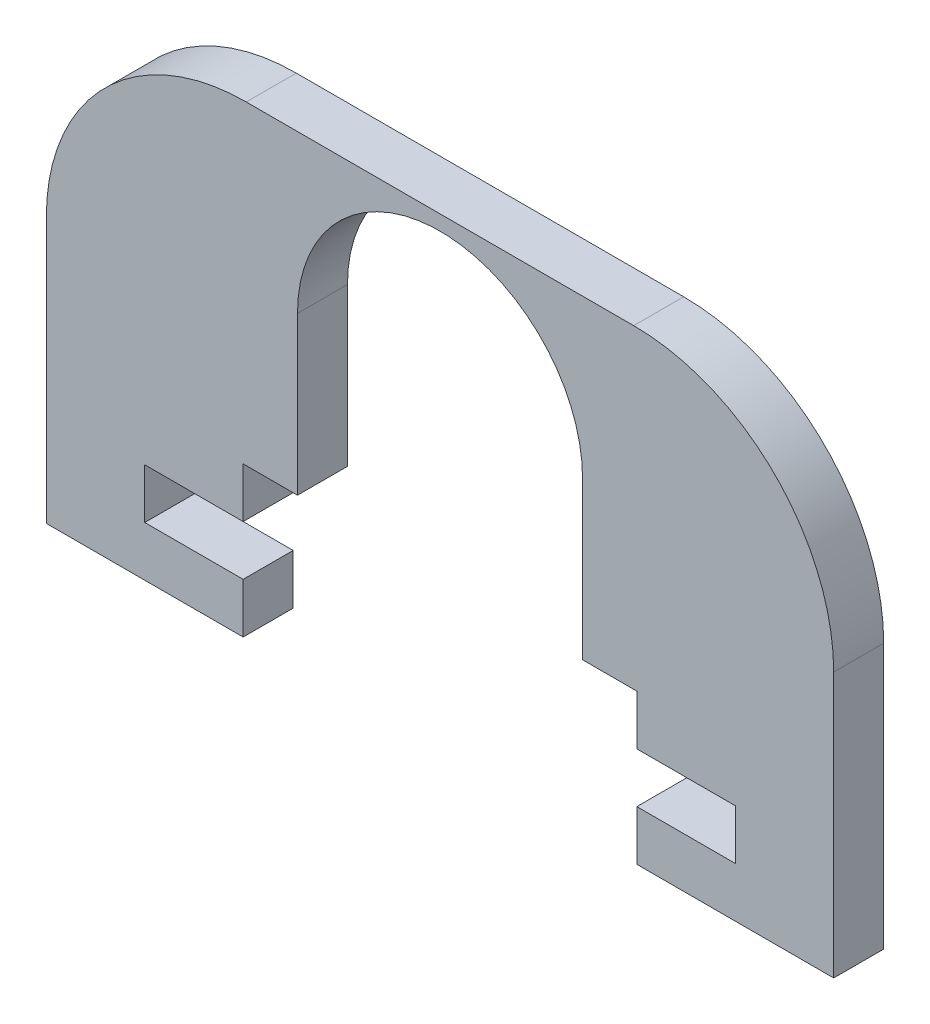
SolidWorks part; units mm, degrees
ref_plane "Front Plane" through (0, 0, 0) normal (0, 0, 1) x (1, 0, 0)
ref_plane "Top Plane" through (0, 0, 0) normal (0, 1, 0) x (1, 0, 0)
ref_plane "Right Plane" through (0, 0, 0) normal (1, 0, 0) x (0, 0, -1)
sketch "Sketch1" plane through (0, 0, 0) normal (0, 0, 1) x (1, 0, 0)
  line L0 (50, 40) -> (50, -12.5863) construction
  line L1 (25, 0) -> (75, 0)
  line L2 (0, 0) -> (0, 40)
  line L3 (0, 40) -> (100, 40)
  line L4 (100, 0) -> (100, 40)
  line L6 (0, 0) -> (0, -6.35)
  line L8 (25, 0) -> (25, -6.35)
  line L10 (75, 0) -> (75, -6.35)
  line L12 (100, 0) -> (100, -6.35)
  line L13 (0, -6.35) -> (0, -19.05)
  line L14 (0, -19.05) -> (25, -19.05)
  line L15 (25, -19.05) -> (25, -6.35)
  line L16 (100, -6.35) -> (100, -19.05)
  line L17 (75, -19.05) -> (75, -6.35)
  line L18 (100, -19.05) -> (75, -19.05)
  dimension "D1" = 100
  dimension "D2" = 40
  dimension "D3" = 6.35
  dimension "D4" = 6.35
  dimension "D5" = 25
  dimension "D6" = 12.7
extrude "Boss-Extrude1" add sketch "Sketch1" along normal blind 6.35
sketch "Sketch2" plane through (0, 0, 6.35) normal (0, 0, 1) x (1, 0, 0)
  line L0 (10, 57.1598) -> (10, -9.9345) construction
  line L1 (0, 40) -> (0, -19.05) construction
  line L2 (50, 0) -> (50, 61.0572) construction
  line L3 (25, 0) -> (75, 0) construction
  line L4 (90, 57.1598) -> (90, -9.9345) construction
  line L6 (100, 40) -> (0, 40) construction
  line L8 (31.921, 40) -> (67.8318, 40)
  line L9 (50, 38.1) -> (50, 6.0702) construction
  line L10 (31.9, 20) -> (68.1, 20) construction
  line L11 (31.9, 20) -> (31.9, 0)
  line L12 (68.1, 20) -> (68.1, 0)
  line L13 (31.9, 0) -> (68.1, 0)
  arc A1 (68.1, 20) -> (31.9, 20) centre (50, 20) ccw
  line M9 (25, 0) -> (75, 0)
  dimension "D2" = 36.2
  dimension "D1" = 10
  dimension "D3" = 20
extrude "Cut-Extrude1" cut sketch "Sketch2" against normal through all both and the other way through all contours L12 A1 L11 M9
fillet "Fillet1" radius 25.4 2 edges at (100, 40, 3.175) (0, 40, 3.175)
sketch "Sketch4" plane through (0, 0, 6.35) normal (0, 0, 1) x (1, 0, 0)
  line L0 (25, 0) -> (25, -6.35)
  line L1 (25, -19.05) -> (25, 0) construction
  line L2 (25, -6.35) -> (12.5, -6.35)
  line L3 (12.5, -6.35) -> (12.5, -12.7)
  line L4 (12.5, -12.7) -> (25, -12.7)
  line L5 (25, -12.7) -> (25, -6.35)
  line L6 (50, 44.499) -> (50, -32.0401) construction
  line L7 (0, 14.6) -> (0, -19.05) construction
  line L8 (75, -12.7) -> (75, -6.35)
  line L9 (87.5, -12.7) -> (75, -12.7)
  line L10 (87.5, -6.35) -> (87.5, -12.7)
  line L11 (75, -6.35) -> (87.5, -6.35)
  line M13 (25, -19.05) -> (25, 0)
  line M19 (75, 0) -> (75, -19.05)
  dimension "D3" = 6.35
  dimension "D1" = 6.35
  dimension "D2" = 12.5
  dimension "D4" = 50
extrude "Cut-Extrude2" cut sketch "Sketch4" against normal through all both and the other way through all contours L3 L4 L2 M13 | L11 L9 L10 M19
equation "\"Wheel Thickness\"= 1in"
equation "\"Wheel Diameter\"= 3in"
equation "\"Motor Rear Diameter\" = 36.2mm"
equation "\"Motor Front Diameter\" = 12mm"
equation "\"Material Thickness\" = .25in"
equation "\"D4@Sketch1\"=\"Material Thickness\""
equation "\"D3@Sketch1\"=\"Material Thickness\""
equation "\"Wheel Cutout Diameter\"= 2cm"
equation "\"Motor Mount Tab Thickness\" = 100mm"
equation "\"D1@Sketch1\"=\"Motor Mount Tab Thickness\""
equation "\"D5@Sketch1\"=(\"Motor Mount Tab Thickness\")/4"
equation "\"D1@Boss-Extrude1\"=\"Material Thickness\""
equation "\"D2@Sketch1\"=\"Motor Mount Tab Height\""
equation "\"Motor Mount Tab Height\" = 40mm"
equation "\"D2@Sketch2\"=\"Motor Rear Diameter\""
equation "\"D3@Sketch2\"=\"Motor Mount Tab Height\"/2"
equation "\"D6@Sketch1\"=\"Material Thickness\"*2"
equation "\"D1@Sketch4\"=\"Material Thickness\""
equation "\"D2@Sketch4\"=\"Motor Mount Tab Thickness\"/8"
equation "\"D3@Sketch4\"=\"Material Thickness\""
equation "\"D4@Sketch4\"=\"Motor Mount Tab Thickness\"/2"
